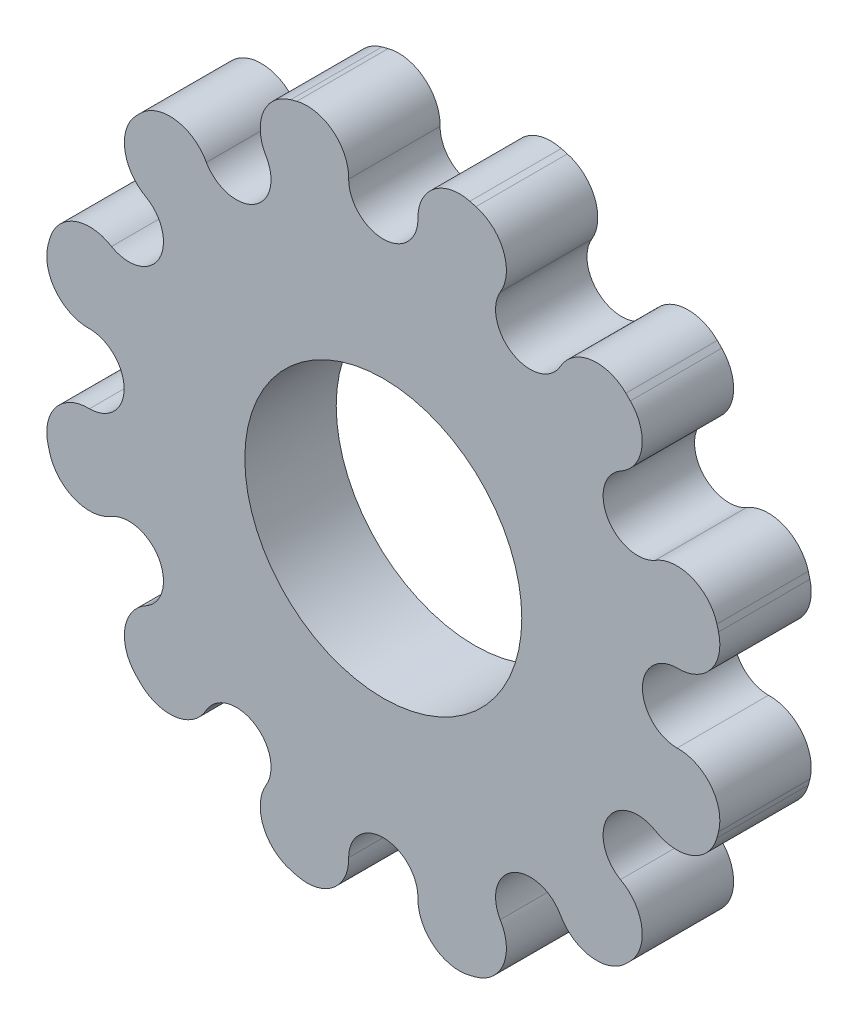
SolidWorks part; units mm, degrees
material "ABS"
ref_plane "Front Plane" through (0, 0, 0) normal (0, 0, 1) x (1, 0, 0)
ref_plane "Top Plane" through (0, 0, 0) normal (0, 1, 0) x (1, 0, 0)
ref_plane "Right Plane" through (0, 0, 0) normal (1, 0, 0) x (0, 0, -1)
sketch "Sketch1" plane through (0, 0, 0) normal (0, 0, 1) x (1, 0, 0)
  circle A0 centre (0, 0) radius 12.7
  circle A1 centre (0, 0) radius 31.75
  dimension "D1" = 25.4
  dimension "D2" = 63.5
extrude "Boss-Extrude1" add sketch "Sketch1" along normal blind 8.382
sketch "Sketch2" plane through (0, 0, 8.382) normal (0, 0, 1) x (1, 0, 0)
  line L0 (-7.9375, 30.7418) -> (-7.9375, 33.9269)
  line L1 (-7.9375, 33.9269) -> (7.9375, 33.9269)
  line L2 (7.9375, 33.9269) -> (7.9375, 30.7418)
  arc A0 (-7.9375, 30.7418) -> (-3.1766, 26.9439) centre (-6.985, 27.0528) cw
  circle A1 centre (0, 0) radius 31.75 construction
  arc A2 (3.1766, 26.9439) -> (7.9375, 30.7418) centre (6.985, 27.0528) cw
  arc A3 (3.1766, 26.9439) -> (-3.1766, 26.9439) centre (0, 26.9439) cw
  dimension "D1" = 3.81
  dimension "D2" = 3.81
  dimension "D5" = 6.985
  dimension "D4" = 6.985
extrude "Cut-Extrude1" cut sketch "Sketch2" against normal blind 11.43
pattern_circular "CirPattern1" count 12 over 360 about axis through (0, 0, 0) along (0, 0, 1) of "Cut-Extrude1"
